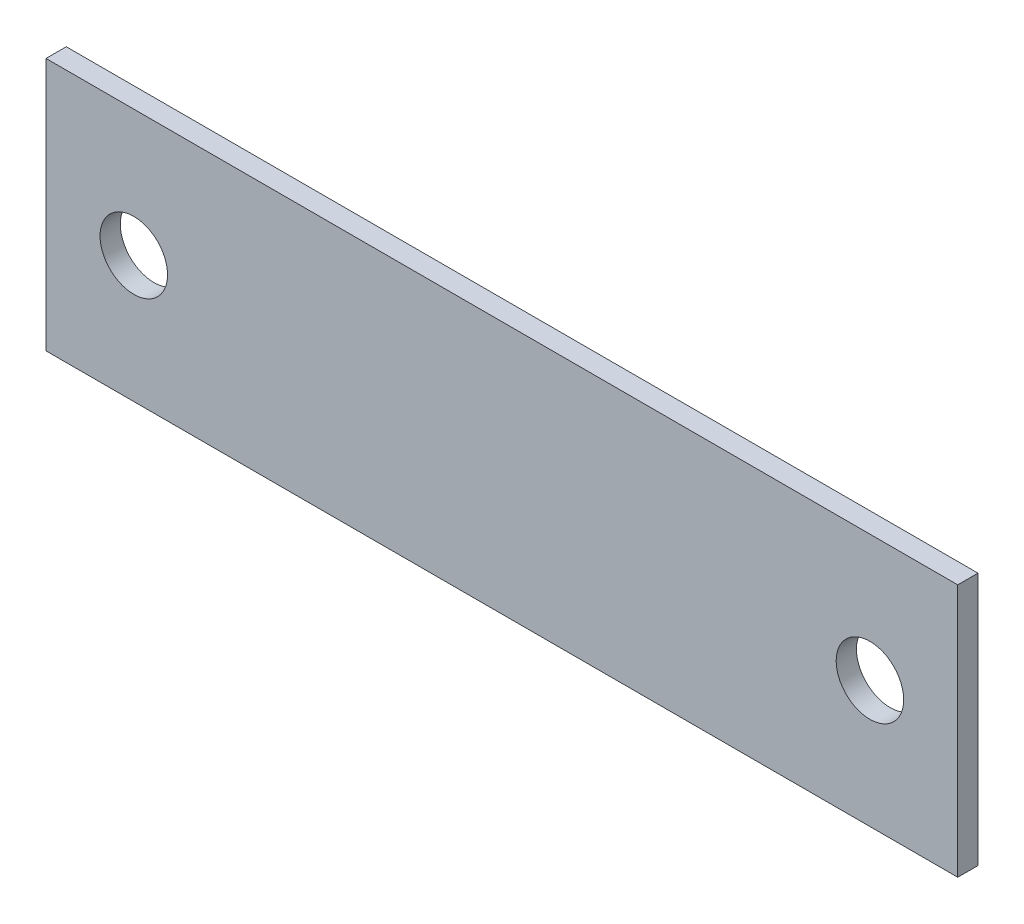
SolidWorks part; units mm, degrees
ref_plane "Plano frontal" through (0, 0, 0) normal (0, 0, 1) x (1, 0, 0)
ref_plane "Plano superior" through (0, 0, 0) normal (0, 1, 0) x (1, 0, 0)
ref_plane "Plano direito" through (0, 0, 0) normal (1, 0, 0) x (0, 0, -1)
sketch "Esboço1" plane through (0, 0, 0) normal (0, 0, 1) x (1, 0, 0)
  line L1 (-27, -7.5) -> (27, -7.5)
  line L2 (-27, -7.5) -> (-27, 7.5)
  line L3 (-27, 7.5) -> (27, 7.5)
  line L4 (27, -7.5) -> (27, 7.5)
  line L5 (-27, -7.5) -> (27, 7.5) construction
  line L6 (-27, 7.5) -> (27, -7.5) construction
  point P0 (0, 0)
  dimension "D1" = 54
  dimension "D2" = 15
extrude "Ressalto-extrusão1" add sketch "Esboço1" along normal blind 1.2
sketch "Esboço2" plane through (0, 0, 0) normal (0, 0, 1) x (1, 0, 0)
  line L0 (-27, 7.5) -> (-27, -7.5) construction
  line L1 (27, -7.5) -> (27, 7.5) construction
  circle A0 centre (-21.8, 0) radius 2
  circle A1 centre (21.8, 0) radius 2
  dimension "D3" = 4
  dimension "D4" = 4
  dimension "D1" = 5.2
  dimension "D2" = 5.2
extrude "Corte-extrusão1" cut sketch "Esboço2" against normal blind 1.2 and the other way blind 5
